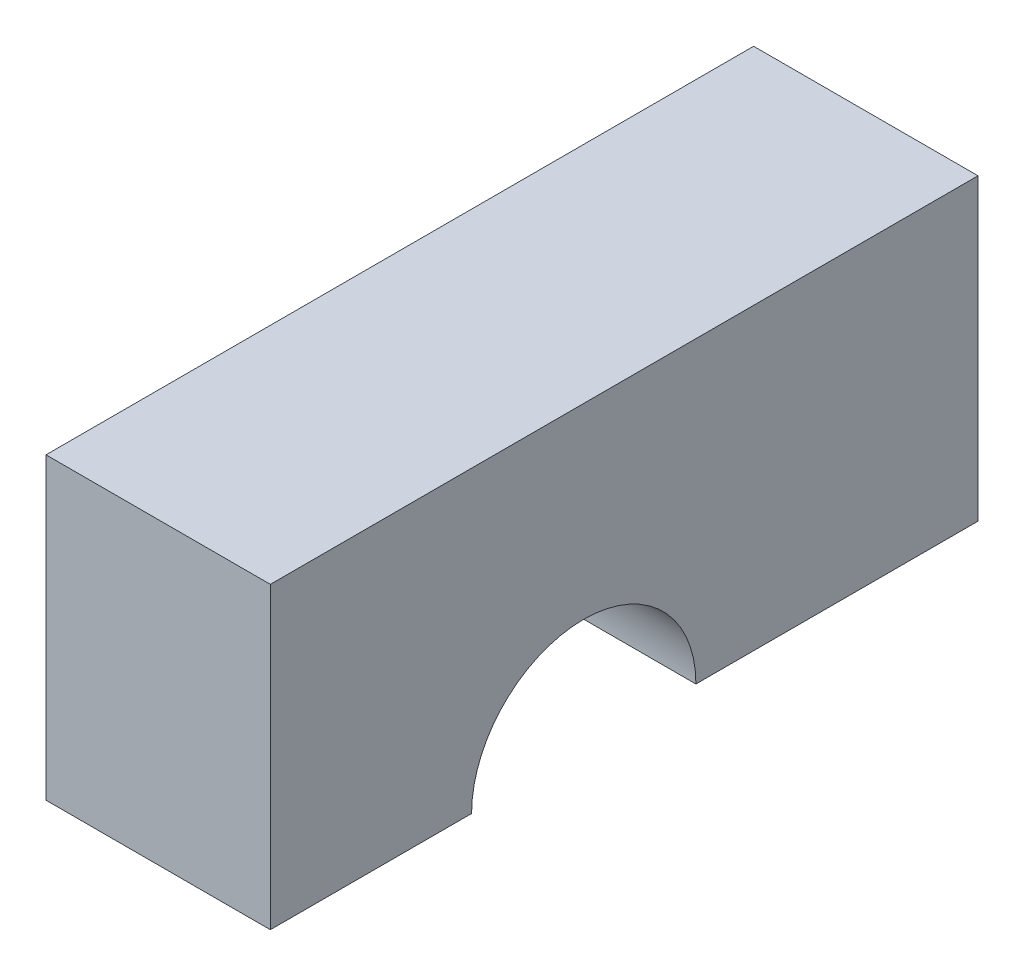
SolidWorks part; units mm, degrees
material "6061 Alloy"
ref_plane "Front Plane" through (0, 0, 0) normal (0, 0, 1) x (1, 0, 0)
ref_plane "Top Plane" through (0, 0, 0) normal (0, 1, 0) x (1, 0, 0)
ref_plane "Right Plane" through (0, 0, 0) normal (1, 0, 0) x (0, 0, -1)
sketch "Sketch1" plane through (0, 0, 0) normal (0, 1, 0) x (1, 0, 0)
  line L0 (-0.236, -42.5519) -> (-16.111, -42.5519) construction
  line L1 (0, -42.5519) -> (-19.05, -42.5519)
  line L2 (0, -42.5519) -> (0, 17.5371)
  line L3 (0, 17.5371) -> (-19.05, 17.5371)
  line L4 (-19.05, -42.5519) -> (-19.05, 17.5371)
  line L5 (-0.236, 17.5371) -> (-19.05, 17.5371) construction
  dimension "D1" = 19.05
extrude "Boss-Extrude1" add sketch "Sketch1" along normal blind 25.4
sketch "Sketch2" plane through (0, 0, 0) normal (1, 0, 0) x (0, 0, -1)
  circle A0 centre (-15.9404, 0) radius 9.525
  arc A1 (-25.4654, 0) -> (-6.4154, 0) centre (-15.9404, 0) ccw construction
  dimension "D1" = 19.05
extrude "Cut-Extrude1" cut sketch "Sketch2" against normal through all
